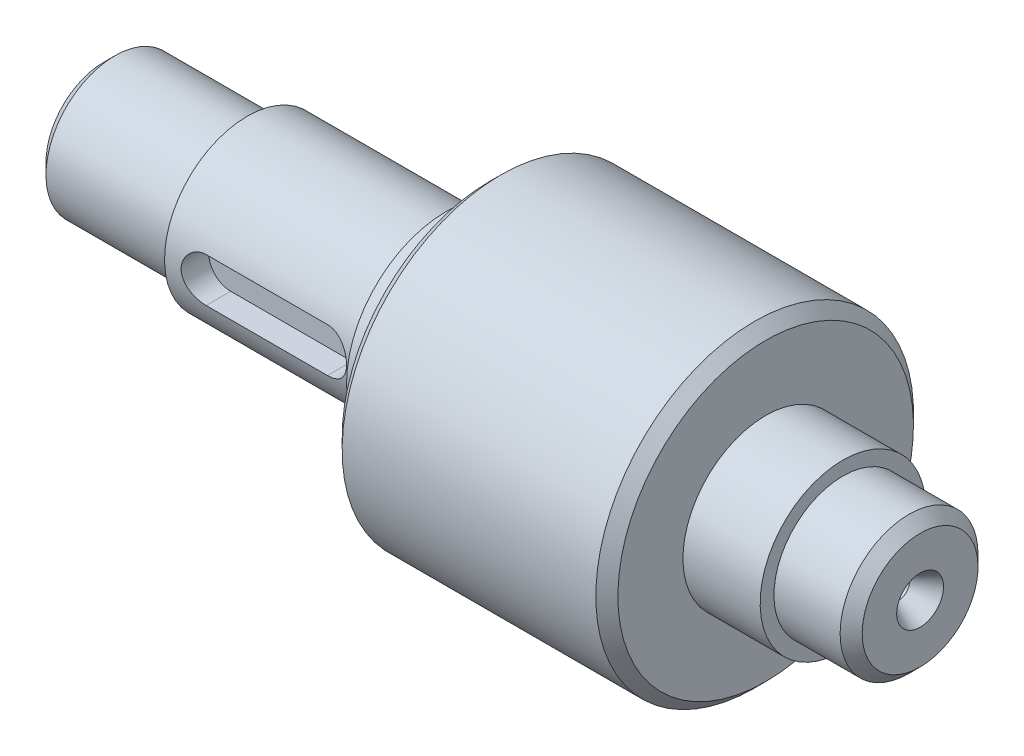
SolidWorks part; units mm, degrees
ref_plane "Спереди" through (0, 0, 0) normal (0, 0, 1) x (1, 0, 0)
ref_plane "Сверху" through (0, 0, 0) normal (0, 1, 0) x (1, 0, 0)
ref_plane "Справа" through (0, 0, 0) normal (1, 0, 0) x (0, 0, -1)
sketch "Эскиз1" plane through (0, 0, 0) normal (0, 0, 1) x (1, 0, 0)
  line L0 (0, 0) -> (0, -12.5)
  line L1 (0, -12.5) -> (26, -12.5)
  line L2 (26, -12.5) -> (26, -15)
  line L3 (26, -15) -> (62, -15)
  line L4 (62, -15) -> (62, -18)
  line L5 (62, -18) -> (70, -18)
  line L6 (70, -18) -> (70, -28.8)
  line L7 (70, -28.8) -> (120, -28.8)
  line L8 (120, -28.8) -> (120, -15)
  line L9 (120, -15) -> (134, -15)
  line L10 (134, -15) -> (134, -12.5)
  line L11 (134, -12.5) -> (148, -12.5)
  line L12 (148, -12.5) -> (148, 0)
  line L13 (148, 0) -> (0, 0)
  point P12 (0, 0)
  point P16 (62, -16.5)
  dimension "D2" = 12.5
  dimension "D3" = 12.5
  dimension "D4" = 15
  dimension "D5" = 18
  dimension "D6" = 28.8
  dimension "D7" = 15
  dimension "D8" = 26
  dimension "D9" = 36
  dimension "D10" = 8
  dimension "D11" = 72
  dimension "D12" = 50
  dimension "D13" = 14
  dimension "D14" = 148
revolve "Повернуть1" add sketch "Эскиз1" angle 360 about L13
sketch "Эскиз3" plane through (0, 0, 0) normal (0, 0, 1) x (1, 0, 0)
  line L0 (0, 0) -> (10.0547, 0)
  line L1 (10.0547, 0) -> (8.9, 2)
  line L2 (8.9, 2) -> (3.9, 2)
  line L3 (3.9, 2) -> (0, 4.25)
  line L4 (0, 12.5) -> (0, -12.5) construction
  line L5 (0, 4.25) -> (0, 0)
  dimension "D1" = 60
  dimension "D2" = 3.9
  dimension "D3" = 5
  dimension "D4" = 4.25
  dimension "D5" = 2
revolve "Вырез-Повернуть1" cut sketch "Эскиз3" angle 360 about L0
ref_plane "Плоскость4" through (74, 0, 0) normal (-1, 0, 0) x (0, 0, 1)
mirror "Зеркальное отражение1" about plane through (74, 0, 0) normal (-1, 0, 0) of "Вырез-Повернуть1"
sketch "Эскиз4" plane through (0, 0, 0) normal (0, 0, 1) x (1, 0, 0)
  line L0 (26, 0) -> (62, 0) construction
  line L1 (26, 12.5) -> (26, -12.5) construction
  line L2 (62, 18) -> (62, -18) construction
  line L3 (33, 0) -> (55, 0) construction
  line L4 (33, 4) -> (55, 4)
  line L5 (33, -4) -> (55, -4)
  arc A0 (33, 4) -> (33, -4) centre (33, 0) ccw
  arc A1 (55, -4) -> (55, 4) centre (55, 0) ccw
  point P8 (44, 0)
  dimension "D1" = 22
  dimension "D2" = 8
extrude "Вырез-Вытянуть2" cut sketch "Эскиз4" along normal through all from offset 10
chamfer "Фаска1" distance 2 angle 45 1 edges at (0, 12.5, 0)
chamfer "Фаска2" distance 2 angle 45 3 edges at (148, 12.5, 0) (120, 28.8, 0) (70, 28.8, 0)
